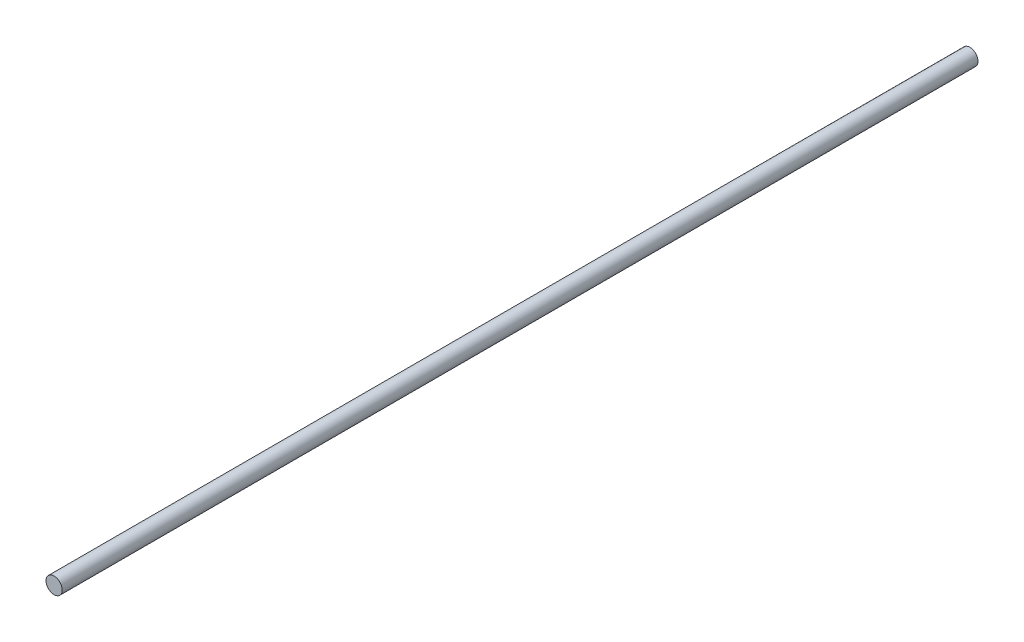
SolidWorks part; units mm, degrees
ref_plane "Front Plane" through (0, 0, 0) normal (0, 0, 1) x (1, 0, 0)
ref_plane "Top Plane" through (0, 0, 0) normal (0, 1, 0) x (1, 0, 0)
ref_plane "Right Plane" through (0, 0, 0) normal (1, 0, 0) x (0, 0, -1)
sketch "Sketch1" plane through (0, 0, 0) normal (0, 0, 1) x (1, 0, 0)
  circle A0 centre (0, 0) radius 2
  dimension "D1" = 4
extrude "Boss-Extrude1" add sketch "Sketch1" along normal mid plane 226
